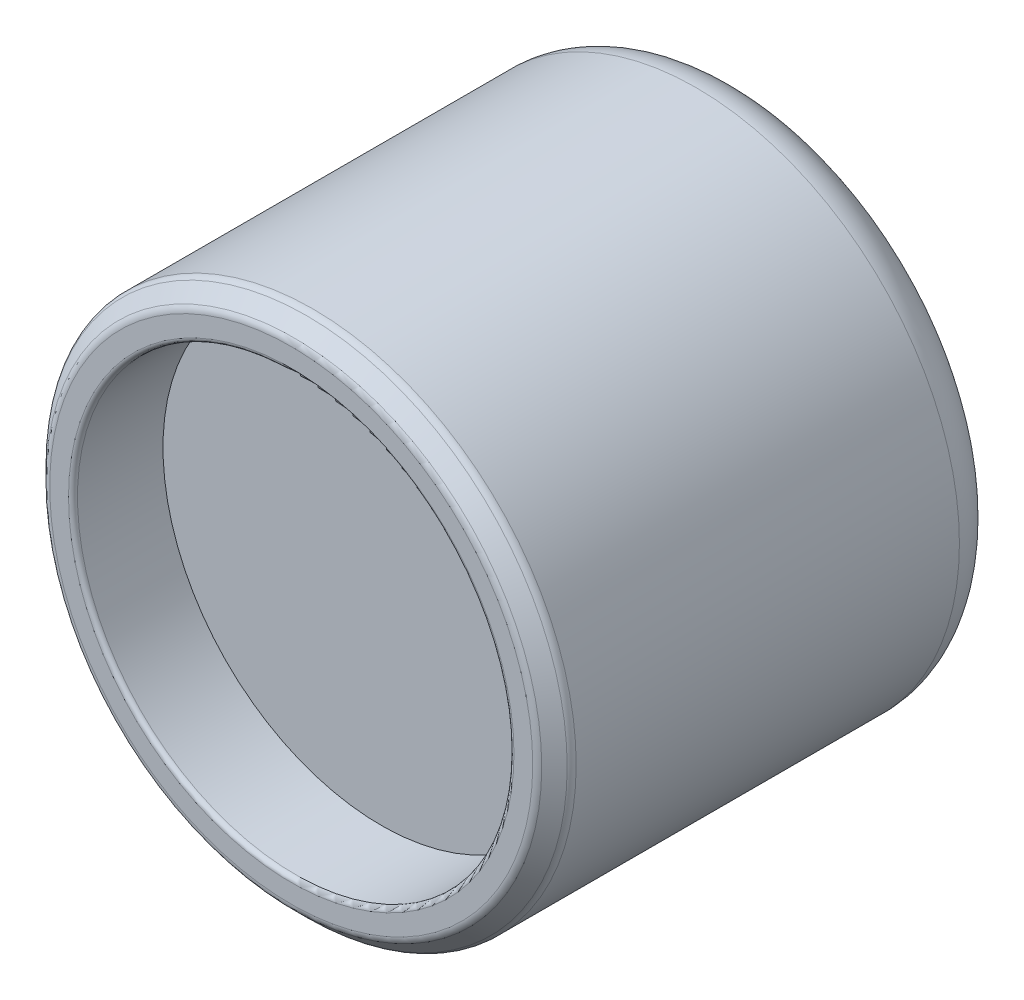
SolidWorks part; units mm, degrees
material "moto_Rubber"
ref_plane "Front Plane" through (0, 0, 0) normal (0, 0, 1) x (1, 0, 0)
ref_plane "Top Plane" through (0, 0, 0) normal (0, 1, 0) x (1, 0, 0)
ref_plane "Right Plane" through (0, 0, 0) normal (1, 0, 0) x (0, 0, -1)
sketch "Sketch1" plane through (0, 0, 0) normal (0, 0, 1) x (1, 0, 0)
  circle A0 centre (0, 0) radius 58.5
  dimension "D1" = 117
extrude "Boss-Extrude2" add sketch "Sketch1" along normal blind 100 contours A0
sketch "Sketch3" plane through (0, 0, 100) normal (0, 0, 1) x (1, 0, 0)
  circle A2 centre (0, 0) radius 48.5
  circle A3 centre (0, 0) radius 48.5
  dimension "D1" = 10
extrude "Cut-Extrude1" cut sketch "Sketch3" against normal blind 20
fillet "Fillet1" radius 1 1 edges at (48.5, 0, 100)
chamfer "Chamfer1" distance 4 angle 45 1 edges at (58.5, 0, 100)
fillet "Fillet3" radius 2 2 edges at (58.5, 0, 96) (54.5, 0, 100)
fillet "Fillet4" radius 10 1 edges at (58.5, 0, 0)
